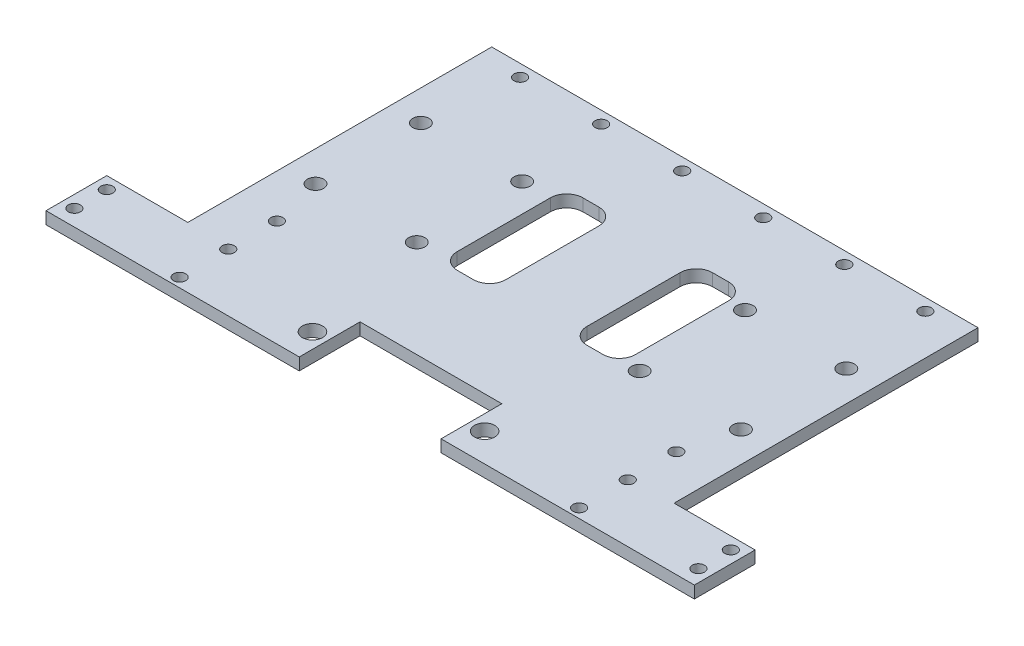
SolidWorks part; units mm, degrees
ref_plane "Alzado" through (0, 0, 0) normal (0, 0, 1) x (1, 0, 0)
ref_plane "Planta" through (0, 0, 0) normal (0, 1, 0) x (1, 0, 0)
ref_plane "Vista lateral" through (0, 0, 0) normal (1, 0, 0) x (0, 0, -1)
sketch "Croquis1" plane through (0, 0, 0) normal (0, 1, 0) x (1, 0, 0)
  line L0 (-80, 17.0002) -> (-80, -106.3361) construction
  line L1 (-20, 0) -> (-140, 0)
  line L2 (0, -20) -> (0, -90)
  line L3 (0, -90) -> (-160, -90)
  line L4 (-160, -20) -> (-160, -90)
  circle A0 centre (-101.245, -83) radius 2.5
  circle A1 centre (-58.755, -83) radius 2.5
  circle A2 centre (-132.5, -25) radius 2
  circle A3 centre (-107.5, -25) radius 2
  circle A4 centre (-107.5, -51) radius 2
  circle A5 centre (-132.5, -51) radius 2
  circle A6 centre (-52.5, -25) radius 2
  circle A7 centre (-27.5, -25) radius 2
  circle A8 centre (-52.5, -51) radius 2
  circle A9 centre (-27.5, -51) radius 2
  arc A10 (-140, 0) -> (-160, -20) centre (-140, -20) ccw
  arc A11 (-20, 0) -> (0, -20) centre (-20, -20) cw
  point P29 (-160, 0)
  point P32 (0, 0)
  dimension "D3" = 42.49
  dimension "D4" = 5
  dimension "D6" = 26
  dimension "D8" = 4
  dimension "D9" = 55
  dimension "D11" = 20
  dimension "D12" = 20
  dimension "D1" = 160
  dimension "D2" = 90
  dimension "D5" = 7
  dimension "D7" = 25
  dimension "D10" = 25
extrude "Saliente-Extruir1" add sketch "Croquis1" along normal blind 3
sketch "Croquis2" plane through (0, 0, 0) normal (0, -1, 0) x (1, 0, 0)
  line L0 (-160, 20) -> (-160, 90) construction
  line L1 (-160, 75) -> (-140, 75)
  line L2 (-160, 75) -> (-160, 0)
  line L3 (-160, 0) -> (-140, 0)
  line L4 (-140, 75) -> (-140, 0)
  line L5 (0, 90) -> (0, 20) construction
  line L6 (0, 75) -> (-20, 75)
  line L7 (0, 75) -> (0, 0)
  line L8 (0, 0) -> (-20, 0)
  line L9 (-20, 75) -> (-20, 0)
  line L10 (-160, 90) -> (0, 90) construction
  line L11 (-20, 0) -> (-140, 0) construction
  line L12 (-80.5836, 103.3603) -> (-80.5836, -21.9198) construction
  dimension "D1" = 20
  dimension "D2" = 20
  dimension "15" = 15
  dimension "D4" = 0
extrude "Cortar-Extruir1" cut sketch "Croquis2" against normal blind 10
sketch "Croquis3" plane through (0, 0, 0) normal (0, -1, 0) x (1, 0, 0)
  line L0 (-160, 90) -> (0, 90) construction
  line L1 (-97.5, 90) -> (-62.5, 90)
  line L2 (-97.5, 90) -> (-97.5, 75)
  line L3 (-97.5, 75) -> (-62.5, 75)
  line L4 (-62.5, 90) -> (-62.5, 75)
  line L5 (-80, 99.8684) -> (-80, -28.3571) construction
  line L6 (-20, 75) -> (-20, 0) construction
  line L7 (-140, 0) -> (-140, 75) construction
  dimension "D1" = 35
  dimension "D2" = 15
extrude "Cortar-Extruir2" cut sketch "Croquis3" against normal blind 10
sketch "Croquis4" plane through (0, 3, 0) normal (0, 1, 0) x (1, 0, 0)
  line L0 (0, -90) -> (0, -75) construction
  line L1 (-62.5, -90) -> (0, -90) construction
  line L2 (-80, 6.182) -> (-80, -118.4352) construction
  line L3 (-20, -75) -> (-20, 0) construction
  line L4 (-140, 0) -> (-140, -75) construction
  circle A0 centre (-30.71, -63.73) radius 1.5
  circle A1 centre (-30.71, -75.73) radius 1.5
  circle A2 centre (-30.71, -87.73) radius 1.5
  circle A3 centre (-129.29, -63.73) radius 1.5
  circle A4 centre (-129.29, -75.73) radius 1.5
  circle A5 centre (-129.29, -87.73) radius 1.5
  dimension "D1" = 30.71
  dimension "D4" = 3
  dimension "D2" = 12
  dimension "D3" = 12
  dimension "D5" = 2.27
extrude "Cortar-Extruir3" cut sketch "Croquis4" against normal blind 10
sketch "Croquis5" plane through (0, 0, 0) normal (0, -1, 0) x (1, 0, 0)
  line L1 (-80, 97.3298) -> (-80, -11.8041) construction
  line L2 (-20, 75) -> (-20, 0) construction
  line L3 (-140, 0) -> (-140, 75) construction
  line L4 (-20, 0) -> (-140, 0) construction
  line L5 (-160, 75) -> (-160, 90) construction
  line L6 (-140, 75) -> (-160, 75) construction
  circle A0 centre (-130, 3) radius 1.5
  circle A1 centre (-110, 3) radius 1.5
  circle A2 centre (-90, 3) radius 1.5
  circle A3 centre (-70, 3) radius 1.5
  circle A4 centre (-50, 3) radius 1.5
  circle A5 centre (-30, 3) radius 1.5
  circle A6 centre (-157, 86) radius 1.5
  circle A7 centre (-157, 78) radius 1.5
  circle A8 centre (-3, 86) radius 1.5
  circle A9 centre (-3, 78) radius 1.5
  point P30 (0, 0)
  dimension "D1" = 20
  dimension "D4" = 3
  dimension "D6" = 3
  dimension "D2" = 60
  dimension "D3" = 100
  dimension "D5" = 3
  dimension "D7" = 3
  dimension "D8" = 3
  dimension "D9" = 8
extrude "Cortar-Extruir4" cut sketch "Croquis5" against normal blind 10
sketch "Croquis6" plane through (0, 0, 0) normal (0, -1, 0) x (-1, 0, 0)
  line L0 (78.5225, -92.0741) -> (78.5225, 15.5035) construction
  line L1 (64.5225, -52) -> (60.5225, -52)
  line L2 (96.5225, -52) -> (92.5225, -52)
  line L3 (100.5225, -48) -> (100.5225, -25)
  line L4 (96.5225, -21) -> (92.5225, -21)
  line L5 (88.5225, -48) -> (88.5225, -25)
  line L6 (68.5225, -48) -> (68.5225, -25)
  line L7 (64.5225, -21) -> (60.5225, -21)
  line L8 (56.5225, -48) -> (56.5225, -25)
  line L9 (20, 0) -> (140, 0) construction
  arc A0 (92.5225, -52) -> (88.5225, -48) centre (92.5225, -48) cw
  arc A1 (96.5225, -52) -> (100.5225, -48) centre (96.5225, -48) ccw
  arc A2 (68.5225, -25) -> (64.5225, -21) centre (64.5225, -25) ccw
  arc A3 (100.5225, -25) -> (96.5225, -21) centre (96.5225, -25) ccw
  arc A4 (92.5225, -21) -> (88.5225, -25) centre (92.5225, -25) ccw
  arc A5 (60.5225, -21) -> (56.5225, -25) centre (60.5225, -25) ccw
  arc A6 (60.5225, -52) -> (56.5225, -48) centre (60.5225, -48) cw
  arc A7 (64.5225, -52) -> (68.5225, -48) centre (64.5225, -48) ccw
  point P10 (94.5225, -21)
  point P15 (88.5225, -52)
  point P18 (100.5225, -52)
  point P23 (100.5225, -21)
  point P32 (68.5225, -52)
  dimension "D5" = 4
  dimension "D6" = 4
  dimension "D7" = 4
  dimension "D8" = 4
  dimension "D9" = 4
  dimension "D1" = 20
  dimension "D2" = 12
  dimension "D3" = 31
  dimension "D4" = 21
extrude "Cortar-Extruir5" cut sketch "Croquis6" against normal blind 10
